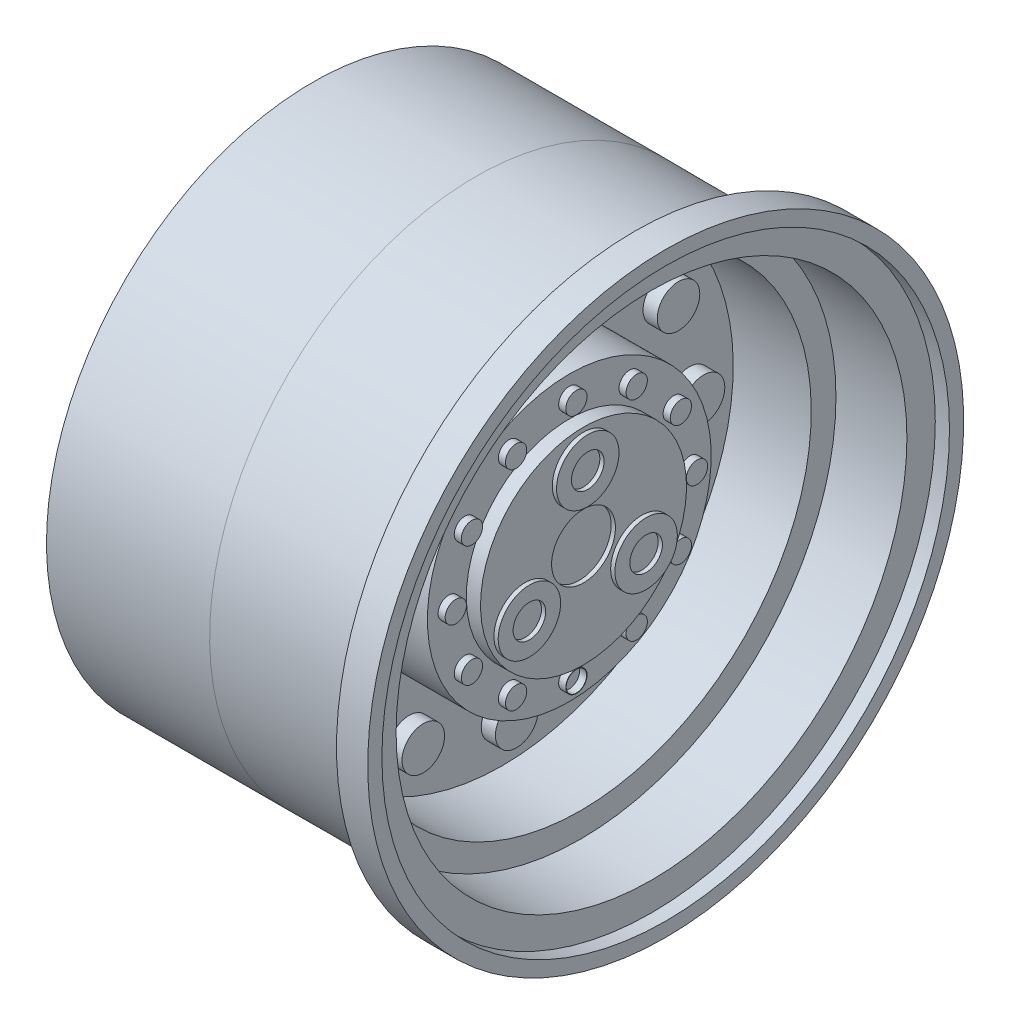
SolidWorks part; units mm, degrees
ref_plane "Front Plane" through (0, 0, 0) normal (0, 0, 1) x (1, 0, 0)
ref_plane "Top Plane" through (0, 0, 0) normal (0, 1, 0) x (1, 0, 0)
ref_plane "Right Plane" through (0, 0, 0) normal (1, 0, 0) x (0, 0, -1)
sketch "Sketch1" plane through (0, 0, 0) normal (0, 0, 1) x (1, 0, 0)
  line L1 (-3.5, 0) -> (3.7942, 0)
  line L2 (-5.75, 9.38) -> (0, 9.38)
  line L3 (-5.75, 9.38) -> (-5.75, 8.5)
  line L4 (-5.75, 8.5) -> (-4.25, 8.5)
  line L5 (-4.25, 8.5) -> (-4.25, 8.13)
  line L6 (-4.25, 8.13) -> (-1.85, 8.13)
  line L7 (-1.85, 8.13) -> (-1.85, 4.5)
  line L8 (-1.85, 4.5) -> (-2.75, 4.5)
  line L9 (-2.75, 4.5) -> (-2.75, 3.25)
  line L10 (-2.75, 3.25) -> (-3.5, 3.25)
  line L11 (-3.5, 3.25) -> (-3.5, 0)
  line L13 (6.69, 10.5) -> (5.59, 10.5)
  line L14 (5.59, 10.5) -> (5.59, 9.3912)
  line L15 (5.59, 9.3912) -> (0, 9.38)
  line L16 (6.69, 10.5) -> (6.69, 10)
  line L17 (6.69, 10) -> (6.19, 10)
  line L18 (6.19, 10) -> (6.19, 9)
  line L19 (3.2942, 5) -> (3.2942, 3.63)
  line L20 (3.2942, 3.63) -> (3.7942, 3.63)
  line L21 (6.19, 9) -> (3.69, 9)
  line L22 (3.7942, 3.63) -> (3.7942, 0)
  line L23 (3.2942, 5) -> (0.94, 5)
  line L26 (3.69, 9) -> (3.69, 8.13)
  line L28 (0.94, 8.13) -> (0.94, 5)
  line L30 (0.94, 8.13) -> (3.69, 8.13)
  dimension "D5" = 3.25
  dimension "D6" = 3.9
  dimension "D7" = 1.5
  dimension "D8" = 2.25
  dimension "D9" = 3
  dimension "D11" = 0.5
  dimension "D12" = 0.5
  dimension "D13" = 1.1
  dimension "D15" = 0.5
  dimension "D16" = 1
  dimension "D17" = 2.5
  dimension "D18" = 0.87
  dimension "D21" = 5.75
  dimension "D22" = 5.75
revolve "Revolve1" add sketch "Sketch1" angle 360 about L1
sketch "Sketch2" plane through (0.94, 0, 0) normal (1, 0, 0) x (0, 0, -1)
  circle A0 centre (0, 0) radius 6.5837 construction
  circle A1 centre (0, 6.5837) radius 0.75
  circle A5 centre (0, -6.5837) radius 0.75
  circle A6 centre (3.2918, 5.7016) radius 0.75
  circle A7 centre (5.7016, 3.2918) radius 0.75
  circle A8 centre (6.5837, 0) radius 0.75
  circle A9 centre (5.7016, -3.2918) radius 0.75
  circle A10 centre (3.2918, -5.7016) radius 0.75
  circle A11 centre (0, -6.5837) radius 0.75
  circle A12 centre (-3.2918, -5.7016) radius 0.75
  circle A13 centre (-5.7016, -3.2918) radius 0.75
  circle A14 centre (-6.5837, 0) radius 0.75
  circle A15 centre (-5.7016, 3.2918) radius 0.75
  circle A16 centre (-3.2918, 5.7016) radius 0.75
  point P7 (0, 0)
  point P32 (0, 0)
  dimension "D1" = 1.5
  dimension "D2" = 1.5
  dimension "D3" = 12
extrude "Boss-Extrude1" add sketch "Sketch2" along normal blind 0.5 contours A16 | A1 | A6 | A7 | A8 | A15 | A13 | A12 | A5 | A9 | A14 | A10
sketch "Sketch3" plane through (3.2942, 0, 0) normal (1, 0, 0) x (0, 0, -1)
  circle A0 centre (0, 0) radius 4.25 construction
  circle A1 centre (0, 4.25) radius 0.375
  circle A2 centre (0, -4.25) radius 0.3603
  circle A3 centre (2.125, 3.6806) radius 0.375
  circle A4 centre (3.6806, 2.125) radius 0.375
  circle A5 centre (4.25, 0) radius 0.375
  circle A6 centre (3.6806, -2.125) radius 0.375
  circle A7 centre (2.125, -3.6806) radius 0.375
  circle A8 centre (0, -4.25) radius 0.375
  circle A9 centre (-2.125, -3.6806) radius 0.375
  circle A10 centre (-3.6806, -2.125) radius 0.375
  circle A11 centre (-4.25, 0) radius 0.375
  circle A12 centre (-3.6806, 2.125) radius 0.375
  circle A13 centre (-2.125, 3.6806) radius 0.375
  point P32 (0, 0)
  dimension "D1" = 8.5
  dimension "D2" = 0.75
  dimension "D3" = 12
extrude "Boss-Extrude2" add sketch "Sketch3" along normal blind 0.25
sketch "Sketch4" plane through (3.7942, 0, 0) normal (1, 0, 0) x (0, 0, -1)
  circle A0 centre (0, 0) radius 1.125
  dimension "D1" = 2.25
extrude "Cut-Extrude2" cut sketch "Sketch4" against normal blind 0.15
sketch "Sketch5" plane through (3.7942, 0, 0) normal (1, 0, 0) x (0, 0, -1)
  circle A0 centre (0, 0) radius 2.375 construction
  circle A1 centre (0, 2.375) radius 0.575
  circle A2 centre (0, 2.375) radius 1.1
  circle A5 centre (0, 0) radius 2.375 construction
  circle A6 centre (2.0568, -1.1875) radius 1.1
  circle A7 centre (2.0568, -1.1875) radius 0.575
  circle A8 centre (0, 0) radius 2.375 construction
  circle A9 centre (-2.0568, -1.1875) radius 1.1
  circle A10 centre (-2.0568, -1.1875) radius 0.575
  point P20 (0, 0)
  dimension "D2" = 2.2
  dimension "D3" = 1.15
  dimension "D4" = 3
extrude "Boss-Extrude3" add sketch "Sketch5" along normal blind 0.15
sketch "Sketch6" plane through (-3.5, 0, 0) normal (-1, 0, 0) x (0, 0, 1)
  circle A1 centre (0, 0) radius 3.81 construction
  circle A2 centre (0, 3.81) radius 0.375
  circle A4 centre (0, 0) radius 3.81 construction
  circle A5 centre (1.905, 3.2996) radius 0.375
  circle A6 centre (0, 0) radius 3.81 construction
  circle A7 centre (3.2996, 1.905) radius 0.375
  circle A8 centre (0, 0) radius 3.81 construction
  circle A9 centre (3.81, 0) radius 0.375
  circle A10 centre (0, 0) radius 3.81 construction
  circle A11 centre (3.2996, -1.905) radius 0.375
  circle A12 centre (0, 0) radius 3.81 construction
  circle A13 centre (1.905, -3.2996) radius 0.375
  circle A14 centre (0, 0) radius 3.81 construction
  circle A15 centre (0, -3.81) radius 0.375
  circle A16 centre (0, 0) radius 3.81 construction
  circle A17 centre (-1.905, -3.2996) radius 0.375
  circle A18 centre (0, 0) radius 3.81 construction
  circle A19 centre (-3.2996, -1.905) radius 0.375
  circle A20 centre (0, 0) radius 3.81 construction
  circle A21 centre (-3.81, 0) radius 0.375
  circle A22 centre (0, 0) radius 3.81 construction
  circle A23 centre (-3.2996, 1.905) radius 0.375
  circle A24 centre (0, 0) radius 3.81 construction
  circle A25 centre (-1.905, 3.2996) radius 0.375
  point P44 (0, 0)
  dimension "D2" = 0.75
  dimension "D3" = 12
extrude "Boss-Extrude4" add sketch "Sketch6" along normal blind 0.25 separate body
sketch "Sketch7" plane through (-3.5, 0, 0) normal (-1, 0, 0) x (0, 0, 1)
  circle A0 centre (0, 0) radius 1.25
  dimension "D1" = 2.5
extrude "Cut-Extrude3" cut sketch "Sketch7" against normal blind 5
